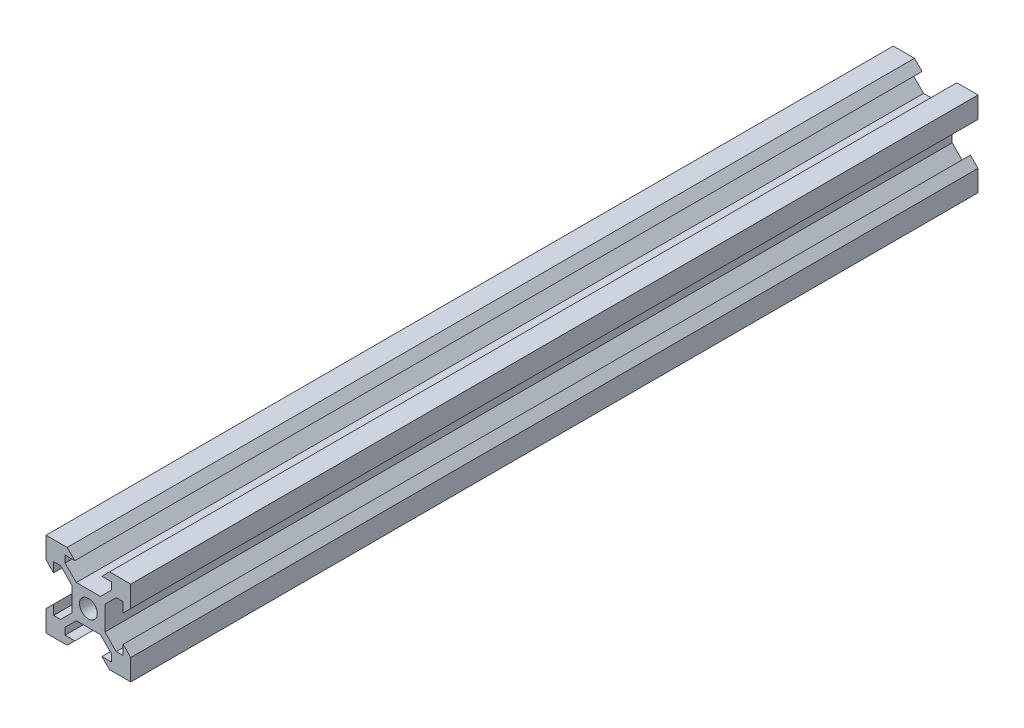
SolidWorks part; units mm, degrees
ref_plane "Front Plane" through (0, 0, 0) normal (0, 0, 1) x (1, 0, 0)
ref_plane "Top Plane" through (0, 0, 0) normal (0, 1, 0) x (1, 0, 0)
ref_plane "Right Plane" through (0, 0, 0) normal (1, 0, 0) x (0, 0, -1)
sketch "Sketch1" plane through (0, 0, 0) normal (0, 0, 1) x (1, 0, 0)
  line L0 (-10, 10) -> (-10, 5)
  line L1 (-10, 5) -> (-8.2, 3.2)
  line L2 (-8.2, 3.2) -> (-8.2, 5.4993)
  line L3 (-8.2, 5.4993) -> (-6.56, 5.4993)
  line L4 (-6.56, 5.4993) -> (-3.9007, 2.84)
  line L5 (-3.9007, 2.84) -> (-3.9007, -2.84)
  line L6 (-3.9007, -2.84) -> (-6.56, -5.4993)
  line L7 (-6.56, -5.4993) -> (-8.2, -5.4993)
  line L8 (-8.2, -5.4993) -> (-8.2, -3.2)
  line L9 (-8.2, -3.2) -> (-10, -5)
  line L10 (-10, -5) -> (-10, -10)
  line L11 (-10, -10) -> (-5, -10)
  line L12 (-5, -10) -> (-3.2, -8.2)
  line L13 (-3.2, -8.2) -> (-5.4993, -8.2)
  line L14 (-5.4993, -8.2) -> (-5.4993, -6.56)
  line L15 (-5.4993, -6.56) -> (-2.84, -3.9007)
  line L16 (-2.84, -3.9007) -> (2.84, -3.9007)
  line L17 (2.84, -3.9007) -> (5.4993, -6.56)
  line L18 (5.4993, -6.56) -> (5.4993, -8.2)
  line L19 (5.4993, -8.2) -> (3.2, -8.2)
  line L20 (3.2, -8.2) -> (5, -10)
  line L21 (5, -10) -> (10, -10)
  line L22 (10, -10) -> (10, -5)
  line L23 (10, -5) -> (8.2, -3.2)
  line L24 (8.2, -3.2) -> (8.2, -5.4993)
  line L25 (8.2, -5.4993) -> (6.56, -5.4993)
  line L26 (6.56, -5.4993) -> (3.9007, -2.84)
  line L27 (3.9007, -2.84) -> (3.9007, 2.84)
  line L28 (3.9007, 2.84) -> (6.56, 5.4993)
  line L29 (6.56, 5.4993) -> (8.2, 5.4993)
  line L30 (8.2, 5.4993) -> (8.2, 3.2)
  line L31 (8.2, 3.2) -> (10, 5)
  line L32 (10, 5) -> (10, 10)
  line L33 (10, 10) -> (5, 10)
  line L34 (5, 10) -> (3.2, 8.2)
  line L35 (3.2, 8.2) -> (5.4993, 8.2)
  line L36 (5.4993, 8.2) -> (5.4993, 6.56)
  line L37 (5.4993, 6.56) -> (2.84, 3.9007)
  line L38 (2.84, 3.9007) -> (-2.84, 3.9007)
  line L39 (-2.84, 3.9007) -> (-5.4993, 6.56)
  line L40 (-5.4993, 6.56) -> (-5.4993, 8.2)
  line L41 (-5.4993, 8.2) -> (-3.2, 8.2)
  line L42 (-3.2, 8.2) -> (-5, 10)
  line L43 (-5, 10) -> (-10, 10)
  circle A0 centre (0, 0) radius 2.1
extrude "Boss-Extrude1" add sketch "Sketch1" against normal blind 200
ref_plane "基准面1" through (0, 0, 0) normal (0, 0, 1) x (1, 0, 0)
